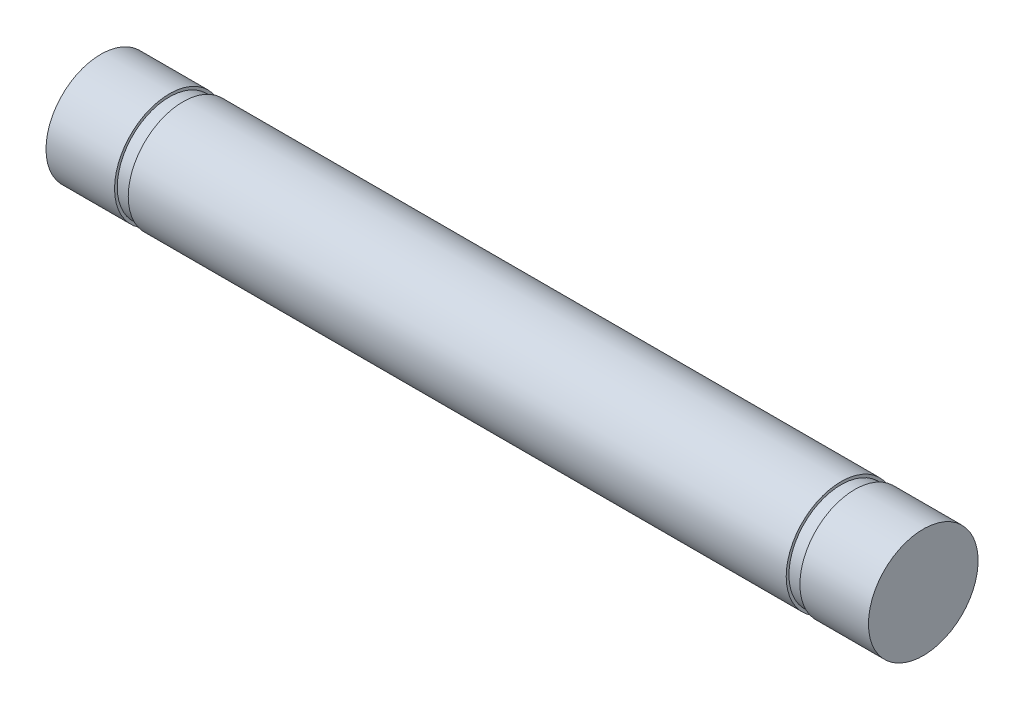
SolidWorks part; units mm, degrees
ref_plane "Ön Düzlem" through (0, 0, 0) normal (0, 0, 1) x (1, 0, 0)
ref_plane "Üst Düzlem" through (0, 0, 0) normal (0, 1, 0) x (1, 0, 0)
ref_plane "Sağ Düzlem" through (0, 0, 0) normal (1, 0, 0) x (0, 0, -1)
sketch "Çizim1" plane through (0, 0, 0) normal (0, 0, 1) x (1, 0, 0)
  line L0 (15, 0) -> (15, 2) construction
  line L1 (0, 0) -> (30, 0)
  line L2 (0, 0) -> (0, 2)
  line L3 (0, 2) -> (2.5, 2)
  line L4 (30, 0) -> (30, 2)
  line L5 (3, 1.9) -> (2.5, 1.9)
  line L6 (3, 1.9) -> (3, 2)
  line L7 (3, 2) -> (27, 2)
  line L8 (2.5, 1.9) -> (2.5, 2)
  line L9 (27, 1.9) -> (27.5, 1.9)
  line L10 (27.5, 1.9) -> (27.5, 2)
  line L11 (27.5, 2) -> (30, 2)
  line L12 (27, 1.9) -> (27, 2)
  dimension "D1" = 2
  dimension "D2" = 30
  dimension "D3" = 2.5
  dimension "D4" = 0.5
  dimension "D5" = 0.1
revolve "Döndür1" add sketch "Çizim1" angle 360 about L1
